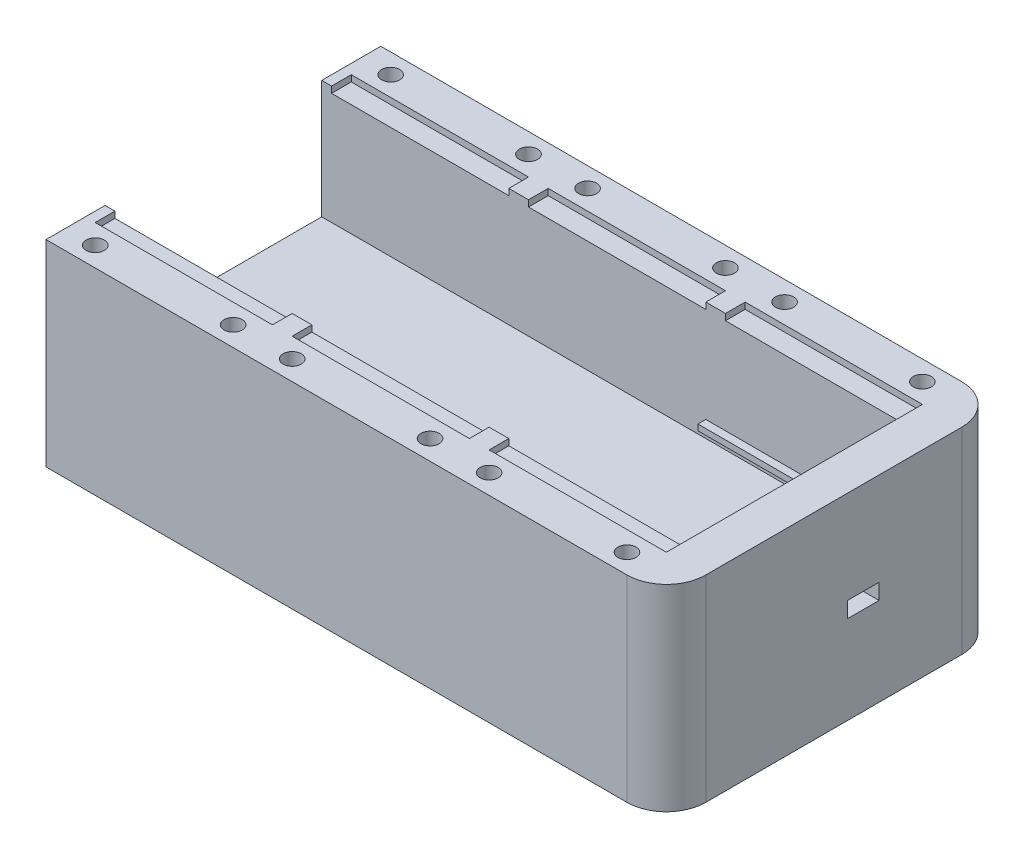
SolidWorks part; units mm, degrees
ref_plane "Ebene vorne" through (0, 0, 0) normal (0, 0, 1) x (1, 0, 0)
ref_plane "Ebene oben" through (0, 0, 0) normal (0, 1, 0) x (1, 0, 0)
ref_plane "Ebene rechts" through (0, 0, 0) normal (1, 0, 0) x (0, 0, -1)
sketch "Skizze2" plane through (0, 0, 0) normal (0, 0, 1) x (1, 0, 0)
  line L1 (0, 0) -> (315, 0)
  line L2 (0, 0) -> (0, 50)
  line L3 (0, 50) -> (315, 50)
  line L4 (315, 0) -> (315, 50)
  dimension "D1" = 315
  dimension "D2" = 50
extrude "Aufsatz-Linear austragen1" add sketch "Skizze2" along normal blind 85
sketch "Skizze4" plane through (0, 50, 0) normal (0, 1, 0) x (1, 0, 0)
  line L0 (315, 0) -> (0, 0) construction
  line L1 (10, -15) -> (305, -15)
  line L2 (10, -15) -> (10, -70)
  line L3 (10, -70) -> (305, -70)
  line L4 (305, -15) -> (305, -70)
  line L5 (315, -85) -> (0, -85) construction
  line L6 (0, -85) -> (0, 0) construction
  line L7 (315, -85) -> (315, 0) construction
  dimension "D1" = 15
  dimension "D2" = 15
  dimension "D3" = 10
  dimension "D4" = 10
extrude "Schnitt-Linear austragen1" cut sketch "Skizze4" against normal blind 30
fillet "Verrundung1" radius 10 1 edges at (315, 25, 0)
fillet "Verrundung2" radius 10 1 edges at (315, 25, 85)
fillet "Verrundung3" radius 10 1 edges at (0, 25, 85)
fillet "Verrundung4" radius 10 1 edges at (0, 25, 0)
sketch "Skizze11" plane through (0, 50, 0) normal (0, 1, 0) x (1, 0, 0)
  line L0 (10, -70) -> (305, -70) construction
  line L1 (10, -15) -> (55, -15)
  line L2 (10, -15) -> (10, -10)
  line L3 (10, -10) -> (55, -10)
  line L4 (55, -15) -> (55, -10)
  line L5 (55, -70) -> (10, -70)
  line L6 (55, -70) -> (55, -75)
  line L7 (55, -75) -> (10, -75)
  line L8 (10, -70) -> (10, -75)
  line L9 (305, -15) -> (10, -15) construction
  line L10 (60, -75) -> (105, -75)
  line L11 (60, -75) -> (60, -70)
  line L12 (60, -70) -> (105, -70)
  line L13 (105, -75) -> (105, -70)
  line L14 (110, -75.0087) -> (155, -75.0087)
  line L15 (110, -75.0087) -> (110, -70)
  line L16 (110, -70) -> (155, -70)
  line L17 (155, -75.0087) -> (155, -70)
  line L18 (160, -75.0087) -> (205, -75.0087)
  line L19 (160, -75.0087) -> (160, -70)
  line L20 (160, -70) -> (205, -70)
  line L21 (205, -75.0087) -> (205, -70)
  line L22 (210, -75) -> (255, -75)
  line L23 (210, -75) -> (210, -70)
  line L24 (210, -70) -> (255, -70)
  line L25 (255, -75) -> (255, -70)
  line L26 (260, -75) -> (305, -75)
  line L27 (260, -75) -> (260, -70)
  line L28 (260, -70) -> (305, -70)
  line L29 (305, -75) -> (305, -70)
  line L30 (305, -15) -> (260, -15)
  line L31 (305, -15) -> (305, -10)
  line L32 (305, -10) -> (260, -10)
  line L33 (260, -15) -> (260, -10)
  line L35 (255, -15) -> (210, -15)
  line L36 (255, -15) -> (255, -10)
  line L37 (255, -10) -> (210, -10)
  line L38 (210, -15) -> (210, -10)
  line L39 (205, -15) -> (160, -15)
  line L40 (205, -15) -> (205, -10)
  line L41 (205, -10) -> (160, -10)
  line L42 (160, -15) -> (160, -10)
  line L43 (155, -15) -> (110, -15)
  line L44 (155, -15) -> (155, -10)
  line L45 (155, -10) -> (110, -10)
  line L46 (110, -15) -> (110, -10)
  line L47 (105, -15) -> (60, -15)
  line L48 (105, -15) -> (105, -10)
  line L49 (105, -10) -> (60, -10)
  line L50 (60, -15) -> (60, -10)
  dimension "D1" = 45
  dimension "D2" = 5
  dimension "D3" = 45
  dimension "D4" = 5
  dimension "D5" = 5
  dimension "D6" = 5
  dimension "D7" = 5
  dimension "D8" = 5
  dimension "D9" = 5
  dimension "D10" = 45
  dimension "D11" = 45
  dimension "D12" = 45
  dimension "D13" = 45
  dimension "D14" = 45
  dimension "D15" = 5
  dimension "D16" = 5
  dimension "D17" = 5
  dimension "D18" = 5
  dimension "D19" = 45
  dimension "D20" = 45
  dimension "D21" = 45
  dimension "D22" = 45
  dimension "D23" = 5
  dimension "D24" = 5
  dimension "D25" = 5
  dimension "D26" = 5
  dimension "D27" = 5
  dimension "D28" = 5
  dimension "D29" = 5
  dimension "D30" = 5
extrude "Schnitt-Linear austragen4" cut sketch "Skizze11" against normal blind 1.6
sketch "Skizze13" plane through (0, 20, 0) normal (0, 1, 0) x (1, 0, 0)
  line L0 (10, -15) -> (10, -70) construction
  line L1 (305, -70) -> (10, -70)
  line L2 (305, -70) -> (305, -67)
  line L3 (305, -67) -> (10, -67)
  line L4 (10, -70) -> (10, -67)
  line L5 (305, -15) -> (10, -15) construction
  dimension "D1" = 52
extrude "Aufsatz-Linear austragen2" add sketch "Skizze13" along normal blind 4.2
sketch "Skizze14" plane through (305, 0, 0) normal (-1, 0, 0) x (0, 0, 1)
  line L0 (15, 20) -> (15, 48.4) construction
  line L1 (31, 26.4) -> (39, 26.4)
  line L2 (31, 26.4) -> (31, 22.4)
  line L3 (31, 22.4) -> (39, 22.4)
  line L4 (39, 26.4) -> (39, 22.4)
  line L5 (67, 20) -> (15, 20) construction
  dimension "D1" = 8
  dimension "D2" = 4
  dimension "D3" = 16
  dimension "D4" = 2.4
extrude "Schnitt-Linear austragen5" cut sketch "Skizze14" against normal blind 19
sketch "Skizze15" plane through (0, 0, 15) normal (0, 0, 1) x (1, 0, 0)
  line L0 (305, 20) -> (305, 48.4) construction
  line L1 (305, 22.7) -> (255, 22.7)
  line L2 (305, 22.7) -> (305, 24.2)
  line L3 (305, 24.2) -> (255, 24.2)
  line L4 (255, 22.7) -> (255, 24.2)
  line L5 (305, 20) -> (10, 20) construction
  dimension "D1" = 50
  dimension "D2" = 1.5
  dimension "D3" = 2.7
extrude "Aufsatz-Linear austragen3" add sketch "Skizze15" along normal blind 2
sketch "Skizze16" plane through (0, 0, 67) normal (0, 0, -1) x (-1, 0, 0)
  line L1 (-305, 24.2) -> (-255, 24.2)
  line L2 (-305, 24.2) -> (-305, 22.7)
  line L3 (-305, 22.7) -> (-255, 22.7)
  line L4 (-255, 24.2) -> (-255, 22.7)
  dimension "D1" = 50
  dimension "D2" = 1.5
extrude "Aufsatz-Linear austragen4" add sketch "Skizze16" along normal blind 2
sketch "Skizze17" plane through (0, 50, 0) normal (0, 1, 0) x (1, 0, 0)
  line L0 (55, -75) -> (55, -70) construction
  line L1 (305, 0) -> (10, 0) construction
  line L2 (305, -85) -> (10, -85) construction
  line L3 (10, -70) -> (10, -75) construction
  line L4 (10, -10) -> (10, -75) construction
  line L5 (55, -15) -> (55, -10) construction
  line L6 (60, -70) -> (60, -75) construction
  line L7 (105, -75) -> (105, -70) construction
  line L8 (155, -75.0087) -> (155, -70) construction
  line L10 (160, -70) -> (160, -75.0087) construction
  line L11 (205, -75.0087) -> (205, -70) construction
  line L12 (305, -75) -> (305, -10) construction
  line L13 (260, -70) -> (260, -75) construction
  line L14 (255, -75) -> (255, -70) construction
  line L15 (210, -70) -> (210, -75) construction
  line L16 (60, -10) -> (60, -15) construction
  line L18 (110, -10) -> (110, -15) construction
  circle A0 centre (50, -80) radius 2.3
  circle A1 centre (15, -80) radius 2.3
  circle A2 centre (15, -5) radius 2.3
  circle A3 centre (50, -5) radius 2.3
  circle A4 centre (65, -5) radius 2.3
  circle A5 centre (99.8349, -5) radius 2.3
  circle A6 centre (65, -80) radius 2.3
  circle A7 centre (100, -80) radius 2.3
  circle A8 centre (114.1455, -79.164) radius 2.3
  circle A9 centre (150, -80) radius 2.3
  circle A10 centre (165, -80) radius 2.3
  circle A11 centre (200, -80) radius 2.3
  circle A12 centre (215, -80) radius 2.3
  circle A13 centre (250, -80) radius 2.3
  circle A14 centre (265, -80) radius 2.3
  circle A15 centre (300, -80) radius 2.3
  circle A16 centre (300, -5) radius 2.3
  circle A17 centre (265, -5) radius 2.3
  circle A18 centre (250, -5) radius 2.3
  circle A19 centre (215, -5) radius 2.3
  circle A20 centre (200, -5) radius 2.3
  circle A21 centre (165, -5) radius 2.3
  circle A22 centre (150, -5) radius 2.3
  circle A23 centre (115, -5) radius 2.3
  dimension "D1" = 4.6
  dimension "D2" = 4.6
  dimension "D3" = 4.6
  dimension "D4" = 4.6
  dimension "D5" = 5
  dimension "D6" = 5
  dimension "D7" = 5
  dimension "D8" = 5
  dimension "D10" = 5
  dimension "D11" = 5
  dimension "D12" = 5
  dimension "D13" = 4.6
  dimension "D14" = 4.6
  dimension "D15" = 4.6
  dimension "D16" = 4.6
  dimension "D17" = 4.6
  dimension "D18" = 4.6
  dimension "D19" = 4.6
  dimension "D20" = 4.6
  dimension "D21" = 4.6
  dimension "D22" = 4.6
  dimension "D23" = 5
  dimension "D25" = 5
  dimension "D26" = 5
  dimension "D27" = 5
  dimension "D28" = 5
  dimension "D29" = 5
  dimension "D30" = 5
  dimension "D31" = 5
  dimension "D32" = 5
  dimension "D33" = 5
  dimension "D34" = 5
  dimension "D35" = 5
  dimension "D36" = 5
  dimension "D37" = 5
  dimension "D38" = 5
  dimension "D39" = 5
  dimension "D40" = 5
  dimension "D41" = 5
  dimension "D42" = 5
  dimension "D43" = 4.6
  dimension "D44" = 4.6
  dimension "D45" = 4.6
  dimension "D46" = 4.6
  dimension "D47" = 4.6
  dimension "D48" = 4.6
  dimension "D49" = 4.6
  dimension "D50" = 4.6
  dimension "D51" = 4.6
  dimension "D52" = 4.6
  dimension "D53" = 5
  dimension "D54" = 5
  dimension "D9" = 5
  dimension "D24" = 5
extrude "Schnitt-Linear austragen6" cut sketch "Skizze17" against normal blind 4
sketch "Skizze18" plane through (0, 50, 0) normal (0, 1, 0) x (1, 0, 0)
  line L0 (305, -85) -> (10, -85) construction
  line L1 (157.5, -85) -> (-14.6643, -85)
  line L2 (157.5, -85) -> (157.5, 0)
  line L3 (157.5, 0) -> (-14.6643, 0)
  line L4 (-14.6643, -85) -> (-14.6643, 0)
extrude "Schnitt-Linear austragen7" cut sketch "Skizze18" against normal blind 80
